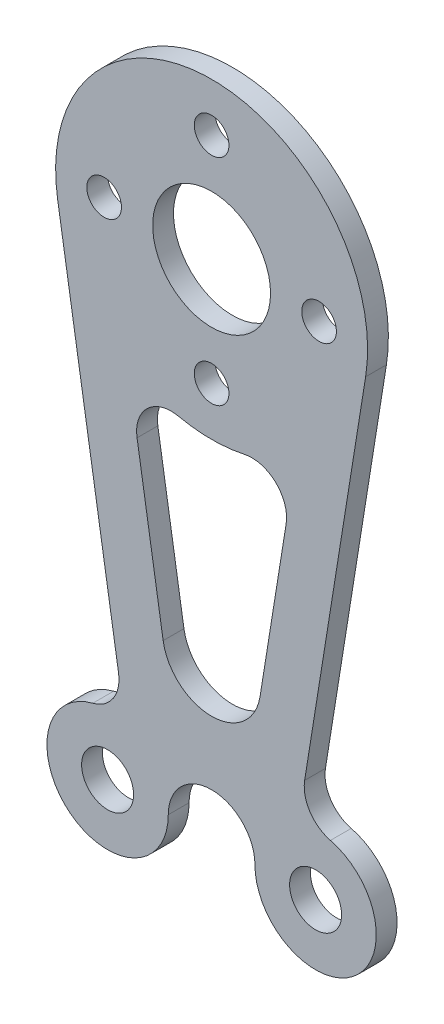
SolidWorks part; units mm, degrees
ref_plane "Front Plane" through (0, 0, 0) normal (0, 0, 1) x (1, 0, 0)
ref_plane "Top Plane" through (0, 0, 0) normal (0, 1, 0) x (1, 0, 0)
ref_plane "Right Plane" through (0, 0, 0) normal (1, 0, 0) x (0, 0, -1)
sketch "Sketch1" plane through (0, 0, 0) normal (0, 0, 1) x (1, 0, 0)
  line L0 (0, 9) -> (0, 3.4) construction
  line L1 (0, -1.0372) -> (0, -16.3901) construction
  line L2 (8.8863, -1.4259) -> (5, -25.6459)
  line L3 (-8.8863, -1.4259) -> (-5, -25.6459)
  line L4 (4.8614, -7.5741) -> (2.7956, -20.4486)
  line L5 (-4.8614, -7.5741) -> (-2.7956, -20.4486)
  line L6 (-5.9242, -0.9506) -> (-2.0379, -25.1706) construction
  line L7 (5.9242, -0.9506) -> (2.0379, -25.1706) construction
  arc A0 (-4.8614, -7.5741) -> (4.8614, -7.5741) centre (0, 0) ccw
  circle A1 centre (0, 0) radius 3.4
  circle A2 centre (0, 6.2) radius 1
  circle A3 centre (6.2, 0) radius 1
  circle A4 centre (0, -6.2) radius 1
  circle A5 centre (-6.2, 0) radius 1
  arc A6 (2.5, -29) -> (5, -25.6459) centre (6, -29) ccw
  circle A7 centre (6, -29) radius 1.5
  circle A8 centre (-6, -29) radius 1.5
  arc A9 (-2.5, -29) -> (-5, -25.6459) centre (-6, -29) cw
  arc A10 (-2.5, -29) -> (2.5, -29) centre (0, -29) cw
  arc A11 (-2.7956, -20.4486) -> (2.7956, -20.4486) centre (0, -20) ccw
  arc A12 (8.8863, -1.4259) -> (-8.8863, -1.4259) centre (0, 0) ccw
  point P8 (0, 6.2)
  point P17 (0, 0)
  dimension "D1" = 18
  dimension "D2" = 6.8
  dimension "D3" = 2
  dimension "D7" = 3
  dimension "D8" = 7
  dimension "D5" = 12
  dimension "D6" = 10
  dimension "D9" = 29
  dimension "D12" = 9
  dimension "D10" = 3
  dimension "D11" = 3
  dimension "D4" = 4
extrude "Boss-Extrude1" add sketch "Sketch1" along normal blind 1.2
fillet "Fillet1" radius 2 4 edges at (-4.8614, -7.5741, 0.6) (4.8614, -7.5741, 0.6) (5, -25.6459, 0.6) (-5, -25.6459, 0.6)
